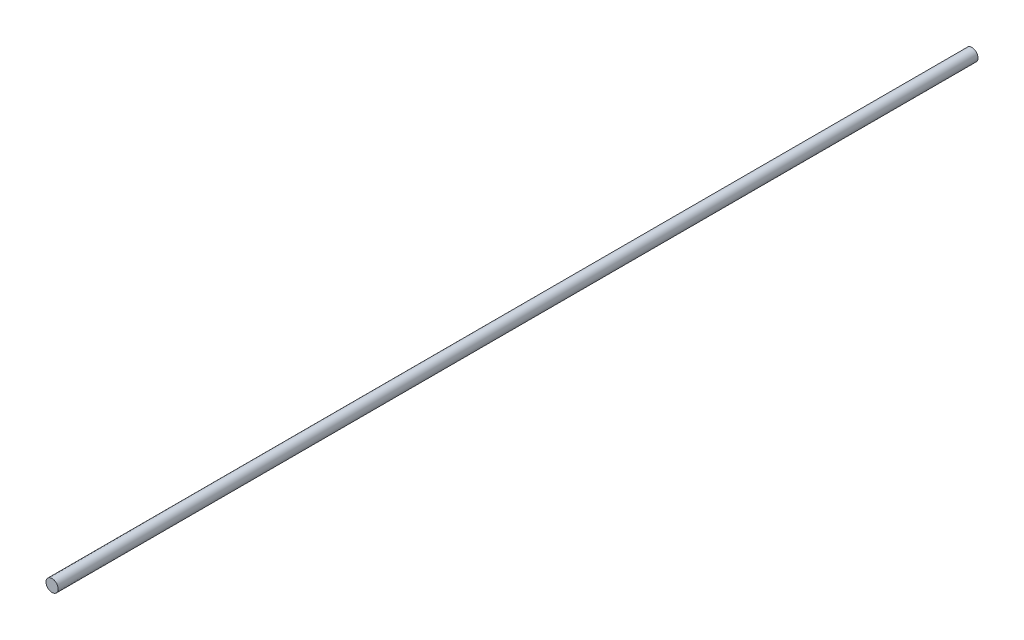
SolidWorks part; units mm, degrees
ref_plane "Front Plane" through (0, 0, 0) normal (0, 0, 1) x (1, 0, 0)
ref_plane "Top Plane" through (0, 0, 0) normal (0, 1, 0) x (1, 0, 0)
ref_plane "Right Plane" through (0, 0, 0) normal (1, 0, 0) x (0, 0, -1)
sketch "Sketch2" plane through (0, 0, 0) normal (0, 0, 1) x (1, 0, 0)
  circle A0 centre (0, 0) radius 1.985
  dimension "D1" = 3.97
extrude "Boss-Extrude1" add sketch "Sketch2" along normal blind 300
